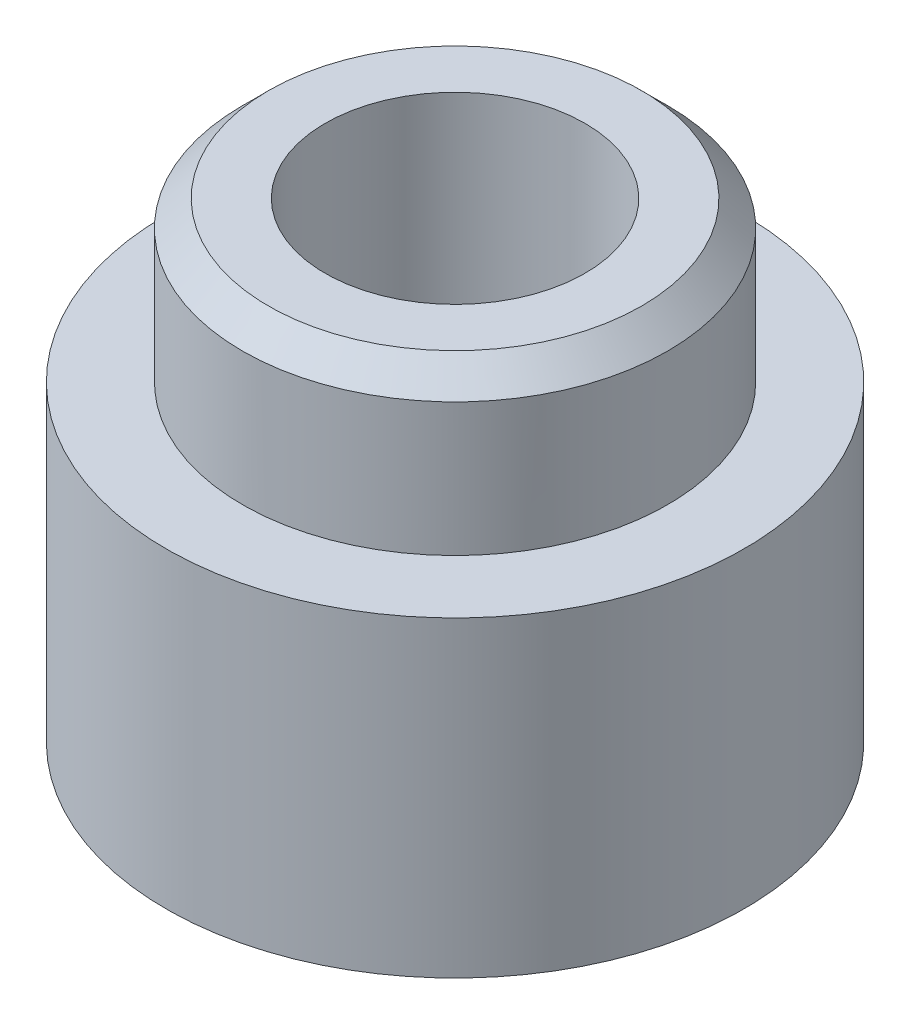
SolidWorks part; units mm, degrees
ref_plane "Front Plane" through (0, 0, 0) normal (0, 0, 1) x (1, 0, 0)
ref_plane "Top Plane" through (0, 0, 0) normal (0, 1, 0) x (1, 0, 0)
ref_plane "Right Plane" through (0, 0, 0) normal (1, 0, 0) x (0, 0, -1)
sketch "Body Sketch" plane through (0, 0, 0) normal (0, 0, 1) x (1, 0, 0)
  line L0 (0, 0) -> (2.78, 0)
  line L1 (2.78, 0) -> (2.78, 3)
  line L2 (2.78, 3) -> (2.045, 3)
  line L3 (2.045, 3) -> (2.045, 4.53)
  line L4 (2.045, 4.53) -> (0, 4.53)
  line L5 (0, 4.53) -> (0, 0)
  dimension "D1" = 1.53
  dimension "D2" = 3
  dimension "D3" = 2.78
  dimension "D4" = 2.045
revolve "Body Revolve" add sketch "Body Sketch" angle 360 about L5
chamfer "Tip Chamfer" distance 0.25 angle 45 1 edges at (-2.045, 4.53, 0)
hole_wizard "M3 Tapped Hole" positions "M3 Tapped Hole Position Sketch" profile "M3 Tapped Hole Profile Sketch" tap size "M3x0.5" standard "ANSI Metric" end condition through all
sketch "M3 Tapped Hole Position Sketch" plane through (0, 0, 0) normal (0, -1, 0) x (-1, 0, 0)
  point P0 (0, 0)
sketch "M3 Tapped Hole Profile Sketch" plane through (0, 0, 0) normal (1, 0, 0) x (0, 0, -1)
  line L0 (0, 0) -> (0, 4.53)
  line L1 (0, 4.53) -> (1.25, 4.53)
  line L2 (1.25, 4.53) -> (1.25, 0)
  line L5 (1.25, 0) -> (0, 0)
  line L11 (0, -6.35) -> (0, 107.95) construction
  dimension "Thru Tap Drill Dia." = 2.5
  dimension "Thru Tap Drill Depth" = 4.53
equation "\"D3@Body Sketch\" = 5.560mm / 2"
equation "\"D4@Body Sketch\" = 4.09 / 2"
